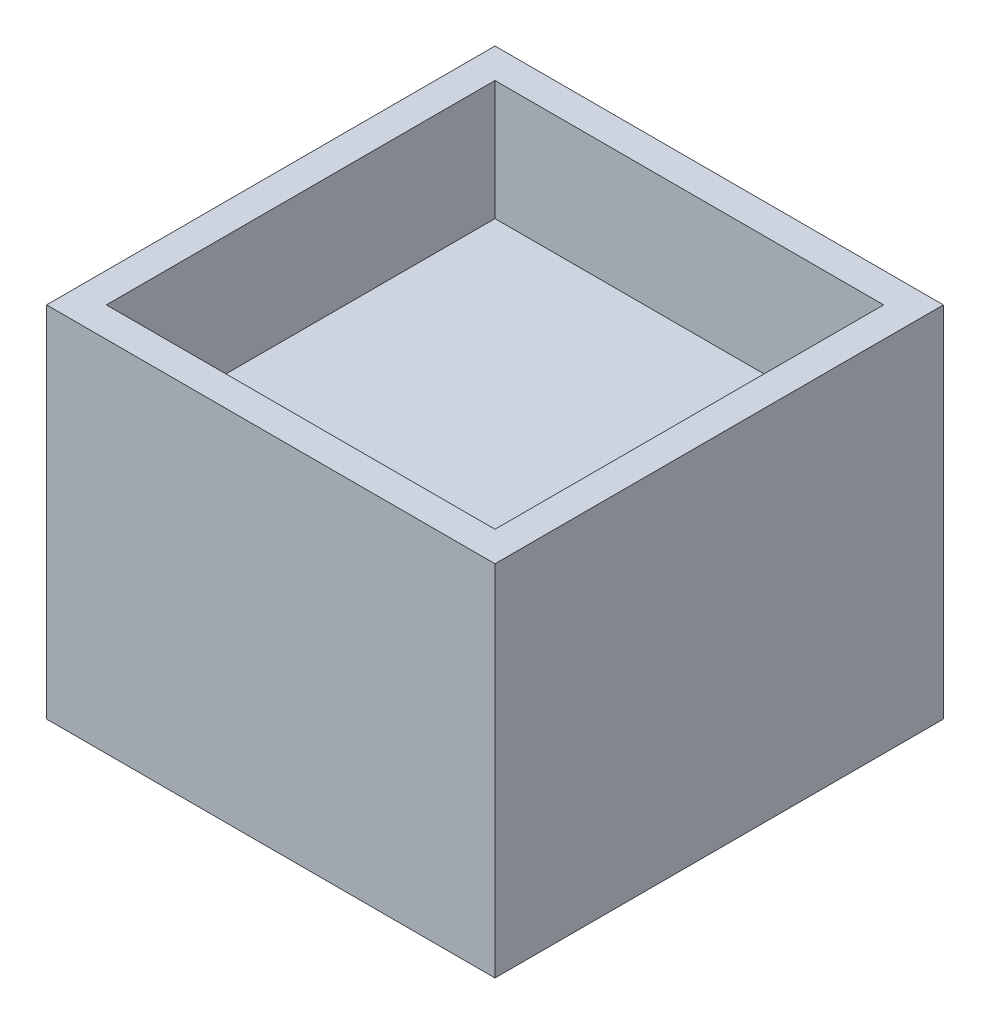
SolidWorks part; units mm, degrees
ref_plane "Front Plane" through (0, 0, 0) normal (0, 0, 1) x (1, 0, 0)
ref_plane "Top Plane" through (0, 0, 0) normal (0, 1, 0) x (1, 0, 0)
ref_plane "Right Plane" through (0, 0, 0) normal (1, 0, 0) x (0, 0, -1)
sketch "Sketch1" plane through (0, 0, 0) normal (0, 1, 0) x (1, 0, 0)
  line L1 (375, -375) -> (-375, -375)
  line L2 (375, -375) -> (375, 375)
  line L3 (375, 375) -> (-375, 375)
  line L4 (-375, -375) -> (-375, 375)
  line L5 (375, -375) -> (-375, 375) construction
  line L6 (375, 375) -> (-375, -375) construction
  point P0 (0, 0)
  dimension "D1" = 750
  dimension "D2" = 750
extrude "Boss-Extrude1" add sketch "Sketch1" along normal blind 600
sketch "Sketch2" plane through (0, 600, 0) normal (0, 1, 0) x (1, 0, 0)
  line L1 (325, -325) -> (-325, -325)
  line L2 (325, -325) -> (325, 325)
  line L3 (325, 325) -> (-325, 325)
  line L4 (-325, -325) -> (-325, 325)
  line L5 (325, -325) -> (-325, 325) construction
  line L6 (325, 325) -> (-325, -325) construction
  line L7 (-375, 375) -> (-375, -375) construction
  line L8 (375, 375) -> (-375, 375) construction
  point P0 (0, 0)
  dimension "D1" = 50
  dimension "D2" = 50
extrude "Cut-Extrude1" cut sketch "Sketch2" against normal blind 200
